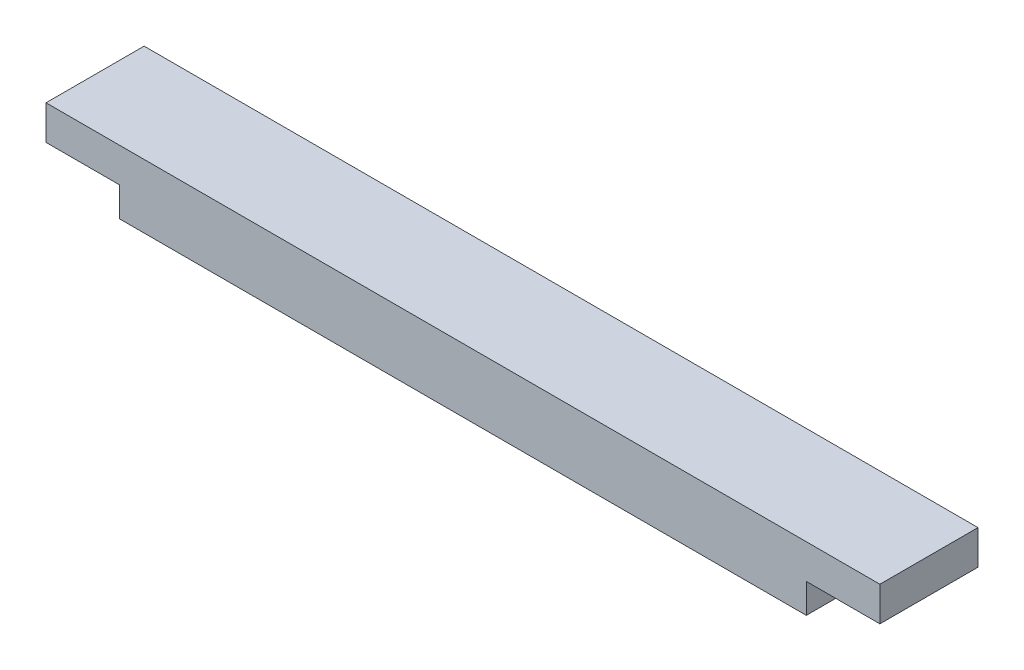
SolidWorks part; units mm, degrees
ref_plane "Ön Düzlem" through (0, 0, 0) normal (0, 0, 1) x (1, 0, 0)
ref_plane "Üst Düzlem" through (0, 0, 0) normal (0, 1, 0) x (1, 0, 0)
ref_plane "Sağ Düzlem" through (0, 0, 0) normal (1, 0, 0) x (0, 0, -1)
sketch "Çizim1" plane through (0, 0, 0) normal (0, 1, 0) x (1, 0, 0)
  line L1 (-70, -10) -> (70, -10)
  line L2 (-70, -10) -> (-70, 10)
  line L3 (-70, 10) -> (70, 10)
  line L4 (70, -10) -> (70, 10)
  line L5 (-70, -10) -> (70, 10) construction
  line L6 (-70, 10) -> (70, -10) construction
  point P0 (0, 0)
extrude "Yükseklik-Ekstrüzyon1" add sketch "Çizim1" along normal blind 6
sketch "Çizim2" plane through (0, 6, 0) normal (0, 1, 0) x (1, 0, 0)
  line L1 (-85, -10) -> (85, -10)
  line L2 (-85, -10) -> (-85, 10)
  line L3 (-85, 10) -> (85, 10)
  line L4 (85, -10) -> (85, 10)
  line L5 (-85, -10) -> (85, 10) construction
  line L6 (-85, 10) -> (85, -10) construction
  point P0 (0, 0)
extrude "Yükseklik-Ekstrüzyon2" add sketch "Çizim2" along normal blind 7
